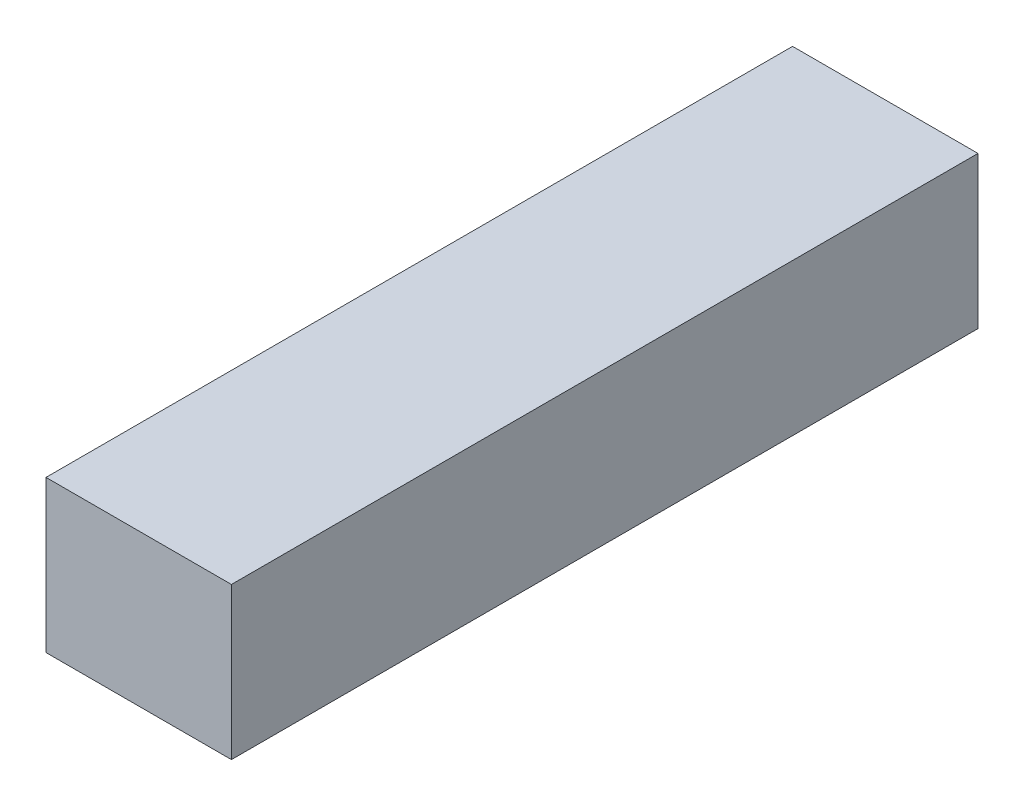
SolidWorks part; units mm, degrees
ref_plane "Front Plane" through (0, 0, 0) normal (0, 0, 1) x (1, 0, 0)
ref_plane "Top Plane" through (0, 0, 0) normal (0, 1, 0) x (1, 0, 0)
ref_plane "Right Plane" through (0, 0, 0) normal (1, 0, 0) x (0, 0, -1)
sketch "Sketch1" plane through (0, 0, 0) normal (0, 0, 1) x (1, 0, 0)
  line L1 (-7.7, -6.3) -> (7.7, -6.3)
  line L2 (-7.7, -6.3) -> (-7.7, 6.3)
  line L3 (-7.7, 6.3) -> (7.7, 6.3)
  line L4 (7.7, -6.3) -> (7.7, 6.3)
  line L5 (-7.7, -6.3) -> (7.7, 6.3) construction
  line L6 (-7.7, 6.3) -> (7.7, -6.3) construction
  point P0 (0, 0)
  dimension "D1" = 15.4
  dimension "D2" = 12.6
extrude "Boss-Extrude1" add sketch "Sketch1" along normal mid plane 62
